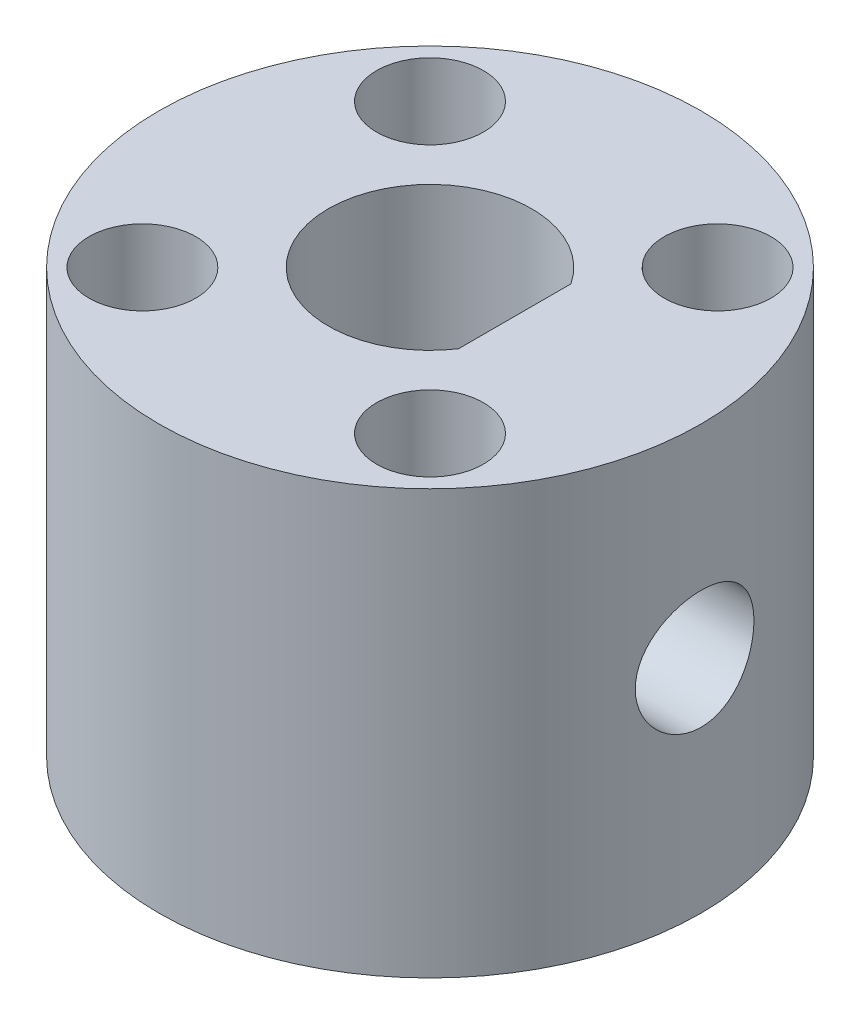
SolidWorks part; units mm, degrees
ref_plane "前视基准面" through (0, 0, 0) normal (0, 0, 1) x (1, 0, 0)
ref_plane "上视基准面" through (0, 0, 0) normal (0, 1, 0) x (1, 0, 0)
ref_plane "右视基准面" through (0, 0, 0) normal (1, 0, 0) x (0, 0, -1)
sketch "草图1" plane through (0, 0, 0) normal (0, 1, 0) x (1, 0, 0)
  line L0 (2.5, 1.6583) -> (2.5, -1.6583)
  line L1 (2.55, 1.6733) -> (2.55, -1.6733) construction
  line L2 (0, 0) -> (4.2426, 4.2426) construction
  arc A0 (2.5, 1.6583) -> (2.5, -1.6583) centre (0, 0) ccw
  circle A1 centre (0, 0) radius 6 construction
  circle A2 centre (4.2426, 4.2426) radius 1.575
  circle A3 centre (4.2426, -4.2426) radius 1.575
  circle A4 centre (-4.2426, -4.2426) radius 1.575
  circle A5 centre (-4.2426, 4.2426) radius 1.575
  circle A6 centre (0, 0) radius 8
  arc A7 (2.55, 1.6733) -> (2.55, -1.6733) centre (0, 0) ccw construction
  point P15 (0, 0)
  point P20 (0, 0)
  dimension "D1" = 6
  dimension "D2" = 12
  dimension "D3" = 3.15
  dimension "D5" = 16
  dimension "D6" = 2.5
  dimension "D7" = 0.05
  dimension "D4" = 4
extrude "凸台-拉伸1" add sketch "草图1" along normal blind 12.5
cosmetic thread "装饰螺纹线2"
cosmetic thread "装饰螺纹线3"
cosmetic thread "装饰螺纹线4"
cosmetic thread "装饰螺纹线5"
sketch "草图2" plane through (0, 12.5, 0) normal (0, 1, 0) x (1, 0, 0)
  circle A0 centre (1.5751, 1.33) radius 1
  circle A1 centre (1.5751, -1.3183) radius 1
  dimension "D1" = 2
  dimension "D2" = 2
sketch "草图3" plane through (2.5, 0, 0) normal (-1, 0, 0) x (0, 0, 1)
  line L0 (5.8176, 12.5) -> (2.6676, 12.5) construction
  circle A0 centre (0, 6.5) radius 1.75
  dimension "D1" = 3.5
  dimension "D2" = 6
extrude "切除-拉伸1" cut sketch "草图3" against normal blind 10
cosmetic thread "装饰螺纹线1" parameters "D2"=5
